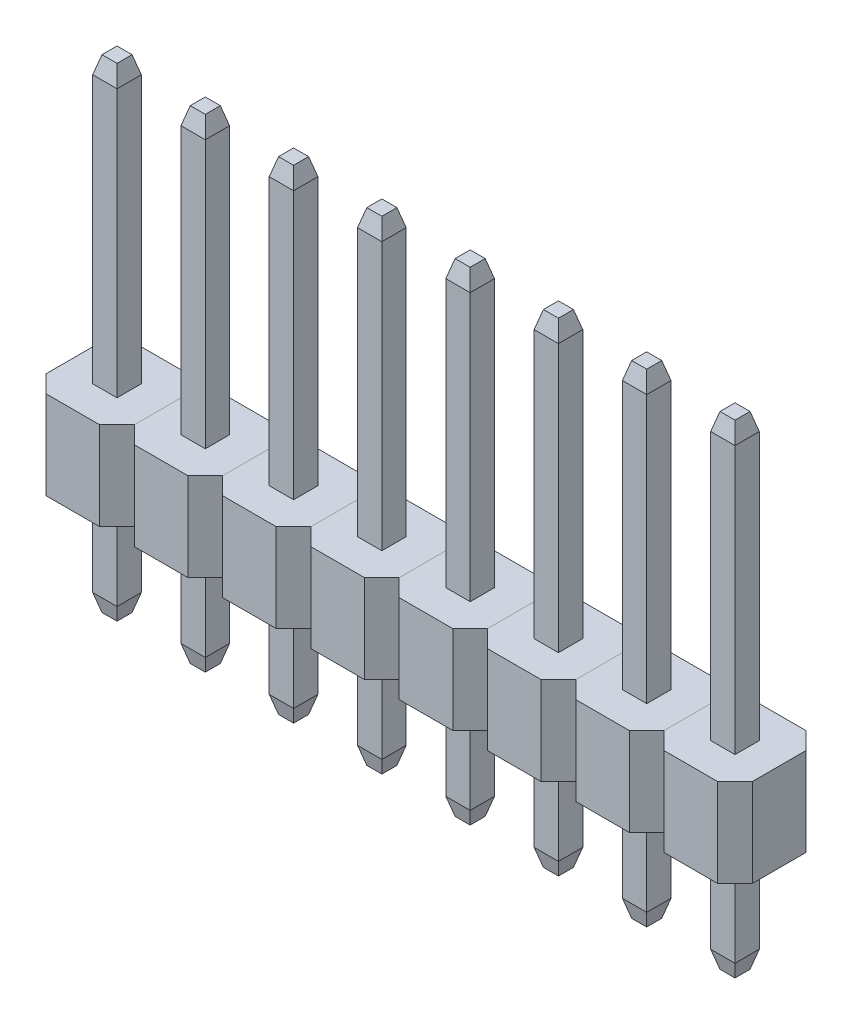
SolidWorks part; units mm, degrees
ref_plane "Front Plane" through (0, 0, 0) normal (0, 0, 1) x (1, 0, 0)
ref_plane "Top Plane" through (0, 0, 0) normal (0, 1, 0) x (1, 0, 0)
ref_plane "Right Plane" through (0, 0, 0) normal (1, 0, 0) x (0, 0, -1)
sketch "Sketch3" plane through (0, 0, 0) normal (0, 1, 0) x (1, 0, 0)
  line L1 (-1.27, 1.27) -> (1.27, 1.27)
  line L2 (-1.27, 1.27) -> (-1.27, -1.27)
  line L3 (-1.27, -1.27) -> (1.27, -1.27)
  line L4 (1.27, 1.27) -> (1.27, -1.27)
  line L5 (-1.27, 1.27) -> (1.27, -1.27) construction
  line L6 (-1.27, -1.27) -> (1.27, 1.27) construction
  line L7 (0.3175, -0.3175) -> (-0.3175, -0.3175)
  line L8 (0.3175, -0.3175) -> (0.3175, 0.3175)
  line L9 (0.3175, 0.3175) -> (-0.3175, 0.3175)
  line L10 (-0.3175, -0.3175) -> (-0.3175, 0.3175)
  line L11 (0.3175, -0.3175) -> (-0.3175, 0.3175) construction
  line L12 (0.3175, 0.3175) -> (-0.3175, -0.3175) construction
  point P0 (0, 0)
  point P7 (0, 0)
  dimension "D1" = 2.54
  dimension "D2" = 0.635
extrude "Boss-Extrude1" add sketch "Sketch3" along normal mid plane 2.54
chamfer "Chamfer1" distance 0.5 angle 45 4 edges at (-1.27, 0, 1.27) (-1.27, 0, -1.27) (1.27, 0, -1.27) (1.27, 0, 1.27)
sketch "Sketch5" plane through (0, 1.27, 0) normal (0, 1, 0) x (1, 0, 0)
  line L1 (0.35, -0.35) -> (-0.35, -0.35)
  line L2 (0.35, -0.35) -> (0.35, 0.35)
  line L3 (0.35, 0.35) -> (-0.35, 0.35)
  line L4 (-0.35, -0.35) -> (-0.35, 0.35)
  line L5 (0.35, -0.35) -> (-0.35, 0.35) construction
  line L6 (0.35, 0.35) -> (-0.35, -0.35) construction
  point P0 (0, 0)
  dimension "D1" = 0.7
extrude "Boss-Extrude2" add sketch "Sketch5" along normal blind 7.7 and the other way blind 5.2 separate body
sketch "Sketch6" plane through (0, 8.97, 0) normal (0, 1, 0) x (1, 0, 0)
  line L4 (-0.35, 0.35) -> (-0.35, -0.35)
  line L5 (-0.35, -0.35) -> (0.35, -0.35)
  line L6 (0.35, -0.35) -> (0.35, 0.35)
  line L7 (0.35, 0.35) -> (-0.35, 0.35)
  line L8 (-0.35, 0.35) -> (-0.35, -0.35)
  line L9 (-0.35, -0.35) -> (0.35, -0.35)
  line L10 (0.35, -0.35) -> (0.35, 0.35)
  line L11 (0.35, 0.35) -> (-0.35, 0.35)
  dimension "D1" = 0
extrude "Boss-Extrude3" add sketch "Sketch6" along normal blind 0.5 draft 15
sketch "Sketch7" plane through (0, -3.93, 0) normal (0, -1, 0) x (1, 0, 0)
  line L4 (-0.35, 0.35) -> (-0.35, -0.35)
  line L5 (-0.35, -0.35) -> (0.35, -0.35)
  line L6 (0.35, -0.35) -> (0.35, 0.35)
  line L7 (0.35, 0.35) -> (-0.35, 0.35)
  line L8 (-0.35, 0.35) -> (-0.35, -0.35)
  line L9 (-0.35, -0.35) -> (0.35, -0.35)
  line L10 (0.35, -0.35) -> (0.35, 0.35)
  line L11 (0.35, 0.35) -> (-0.35, 0.35)
  dimension "D1" = 0
extrude "Boss-Extrude4" add sketch "Sketch7" along normal blind 0.5 draft 15
pattern_linear "LPattern1" count 8 spacing 2.54 along (1, 0, 0) of "Boss-Extrude1", "Boss-Extrude2"
